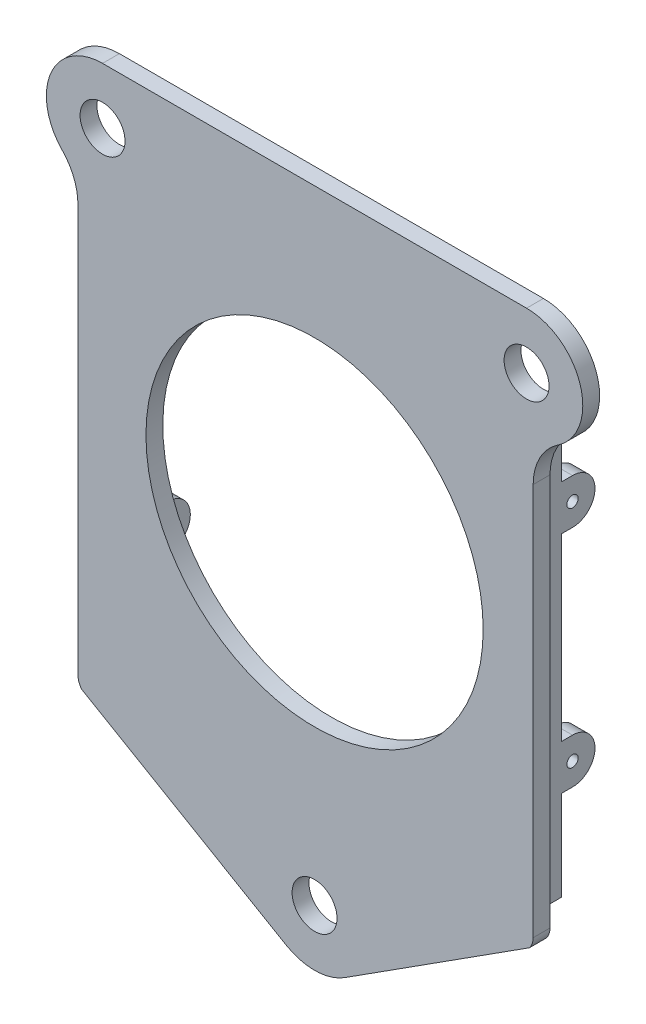
SolidWorks part; units mm, degrees
ref_plane "Front Plane" through (0, 0, 0) normal (0, 0, 1) x (1, 0, 0)
ref_plane "Top Plane" through (0, 0, 0) normal (0, 1, 0) x (1, 0, 0)
ref_plane "Right Plane" through (0, 0, 0) normal (1, 0, 0) x (0, 0, -1)
sketch "Sketch1" plane through (0, 0, 105.6016) normal (0, 0, 1) x (1, 0, 0)
  line L10 (93.8452, 26.6285) -> (97.7185, 26.6285)
  line L11 (98.3949, 28.5261) -> (98.3949, 105.9568)
  line L12 (95.3949, 108.9568) -> (20.3949, 108.9568)
  line L13 (17.3949, 105.9568) -> (17.3949, 28.5261)
  line L14 (18.0713, 26.6285) -> (21.9446, 26.6285)
  line L15 (21.9446, 26.6285) -> (20.8459, 27.9739)
  line L16 (20.3949, 29.239) -> (20.3949, 103.9568)
  line L17 (22.3949, 105.9568) -> (93.3949, 105.9568)
  line L18 (95.3949, 103.9568) -> (95.3949, 29.239)
  line L19 (94.944, 27.9739) -> (93.8452, 26.6285)
  line L20 (93.8452, 26.6285) -> (97.7185, 26.6285)
  line L21 (98.3949, 28.5261) -> (98.3949, 105.9568)
  line L22 (95.3949, 108.9568) -> (20.3949, 108.9568)
  line L23 (17.3949, 105.9568) -> (17.3949, 28.5261)
  line L24 (18.0713, 26.6285) -> (21.9446, 26.6285)
  line L25 (21.9446, 26.6285) -> (20.8459, 27.9739)
  line L26 (20.3949, 29.239) -> (20.3949, 103.9568)
  line L27 (22.3949, 105.9568) -> (93.3949, 105.9568)
  line L28 (95.3949, 103.9568) -> (95.3949, 29.239)
  line L29 (94.944, 27.9739) -> (93.8452, 26.6285)
  arc A8 (97.7185, 26.6285) -> (98.3949, 28.5261) centre (95.3949, 28.5261) ccw
  arc A9 (98.3949, 105.9568) -> (95.3949, 108.9568) centre (95.3949, 105.9568) ccw
  arc A10 (20.3949, 108.9568) -> (17.3949, 105.9568) centre (20.3949, 105.9568) ccw
  arc A11 (17.3949, 28.5261) -> (18.0713, 26.6285) centre (20.3949, 28.5261) ccw
  arc A12 (20.3949, 29.239) -> (20.8459, 27.9739) centre (22.3949, 29.239) ccw
  arc A13 (22.3949, 105.9568) -> (20.3949, 103.9568) centre (22.3949, 103.9568) ccw
  arc A14 (95.3949, 103.9568) -> (93.3949, 105.9568) centre (93.3949, 103.9568) ccw
  arc A15 (94.944, 27.9739) -> (95.3949, 29.239) centre (93.3949, 29.239) ccw
  arc A16 (97.7185, 26.6285) -> (98.3949, 28.5261) centre (95.3949, 28.5261) ccw
  arc A17 (98.3949, 105.9568) -> (95.3949, 108.9568) centre (95.3949, 105.9568) ccw
  arc A18 (20.3949, 108.9568) -> (17.3949, 105.9568) centre (20.3949, 105.9568) ccw
  arc A19 (17.3949, 28.5261) -> (18.0713, 26.6285) centre (20.3949, 28.5261) ccw
  arc A20 (20.3949, 29.239) -> (20.8459, 27.9739) centre (22.3949, 29.239) ccw
  arc A21 (22.3949, 105.9568) -> (20.3949, 103.9568) centre (22.3949, 103.9568) ccw
  arc A22 (95.3949, 103.9568) -> (93.3949, 105.9568) centre (93.3949, 103.9568) ccw
  arc A23 (94.944, 27.9739) -> (95.3949, 29.239) centre (93.3949, 29.239) ccw
  dimension "D1" = 0
extrude "Casing edge profile" add sketch "Sketch1" along normal blind 3
sketch "Sketch2" plane through (0, 0, 108.6016) normal (0, 0, 1) x (1, 0, 0)
  line L0 (97.2224, 124.9411) -> (21.7756, 124.9411)
  line L1 (97.7185, 26.6285) -> (64.8887, 5.6221)
  line L2 (18.0713, 26.6285) -> (54.4613, 5.4069)
  line L3 (98.3949, 28.5261) -> (98.3949, 105.9568) construction
  line L4 (98.3949, 28.5261) -> (98.3949, 98.3528)
  line L5 (17.3949, 105.9568) -> (17.3949, 28.5261) construction
  line L6 (17.3949, 105.9568) -> (17.3949, 28.5261)
  circle A0 centre (97.2224, 114.9411) radius 4 construction
  circle A1 centre (21.7756, 114.9411) radius 4 construction
  circle A2 centre (97.2224, 114.9411) radius 4
  circle A3 centre (21.7756, 114.9411) radius 4
  circle A4 centre (59.499, 14.0453) radius 4 construction
  circle A5 centre (59.499, 14.0453) radius 4
  arc A6 (54.4613, 5.4069) -> (64.8887, 5.6221) centre (59.499, 14.0453) ccw
  arc A7 (102.8087, 106.647) -> (97.2224, 124.9411) centre (97.2224, 114.9411) ccw
  arc A8 (21.7756, 124.9411) -> (17.3949, 105.9517) centre (21.7756, 114.9411) ccw
  circle A9 centre (59.499, 14.0453) radius 10 construction
  arc A10 (97.7185, 26.6285) -> (98.3949, 28.5261) centre (95.3949, 28.5261) ccw construction
  arc A11 (97.7185, 26.6285) -> (98.3949, 28.5261) centre (95.3949, 28.5261) ccw
  arc A12 (17.3949, 28.5261) -> (18.0713, 26.6285) centre (20.3949, 28.5261) ccw construction
  arc A13 (17.3949, 28.5261) -> (18.0713, 26.6285) centre (20.3949, 28.5261) ccw
  circle A14 centre (97.2224, 114.9411) radius 10 construction
  circle A15 centre (21.7756, 114.9411) radius 10 construction
  arc A16 (98.3949, 98.3528) -> (102.8087, 106.647) centre (108.3949, 98.3528) cw
  point P14 (429.1037, 262.7196)
  line M8 (94.944, 27.9739) -> (93.8452, 26.6285)
  line M9 (93.8452, 26.6285) -> (97.7185, 26.6285)
  arc M10 (97.7185, 26.6285) -> (98.3949, 28.5261) centre (95.3949, 28.5261) ccw
  line M11 (98.3949, 28.5261) -> (98.3949, 105.9568)
  arc M12 (98.3949, 105.9568) -> (95.3949, 108.9568) centre (95.3949, 105.9568) ccw
  line M13 (95.3949, 108.9568) -> (20.3949, 108.9568)
  arc M14 (20.3949, 108.9568) -> (17.3949, 105.9568) centre (20.3949, 105.9568) ccw
  line M15 (17.3949, 105.9568) -> (17.3949, 28.5261)
  arc M16 (17.3949, 28.5261) -> (18.0713, 26.6285) centre (20.3949, 28.5261) ccw
  line M17 (18.0713, 26.6285) -> (21.9446, 26.6285)
  line M18 (21.9446, 26.6285) -> (20.8459, 27.9739)
  arc M19 (20.8459, 27.9739) -> (20.3949, 29.239) centre (22.3949, 29.239) cw
  line M20 (20.3949, 29.239) -> (20.3949, 103.9568)
  arc M21 (20.3949, 103.9568) -> (22.3949, 105.9568) centre (22.3949, 103.9568) cw
  line M22 (22.3949, 105.9568) -> (93.3949, 105.9568)
  arc M23 (93.3949, 105.9568) -> (95.3949, 103.9568) centre (93.3949, 103.9568) cw
  line M24 (95.3949, 103.9568) -> (95.3949, 29.239)
  arc M25 (95.3949, 29.239) -> (94.944, 27.9739) centre (93.3949, 29.239) cw
  dimension "D2" = 10
  dimension "D1" = 6
extrude "Screwholes and other stuff" add sketch "Sketch2" against normal blind 3 contours A16 A7 L0 A8 A2 A3 M11 M15 M14 M13 M12 | L6 M25 M8 M9 M10 M11 M12 M13 M14 M15 M16 M17 M18 M19 M20 M21 M22 M23 M24 | L2 A6 L1 A5 M9 M8 M25 M24 M23 M22 M21 M20 M19 M18 M17
sketch "Sketch3" plane through (0, 0, 105.6016) normal (0, 0, -1) x (-1, 0, 0)
  line L0 (-20.3949, 103.9568) -> (-20.3949, 29.239) construction
  line L1 (-20.3949, 103.9568) -> (-20.3949, 29.239)
  line L2 (-93.3949, 105.9568) -> (-22.3949, 105.9568) construction
  line L3 (-93.3949, 105.9568) -> (-22.3949, 105.9568)
  line L4 (-95.3949, 29.239) -> (-95.3949, 103.9568) construction
  line L5 (-95.3949, 29.239) -> (-95.3949, 103.9568)
  line L6 (-23.3949, 102.9568) -> (-23.3949, 29.239)
  line L7 (-92.3949, 102.9568) -> (-23.3949, 102.9568)
  line L8 (-92.3949, 29.239) -> (-92.3949, 102.9568)
  line L9 (-95.3949, 29.239) -> (-92.3949, 29.239)
  line L10 (-23.3949, 29.239) -> (-20.3949, 29.239)
  arc A0 (-20.3949, 103.9568) -> (-22.3949, 105.9568) centre (-22.3949, 103.9568) ccw construction
  arc A1 (-20.3949, 103.9568) -> (-22.3949, 105.9568) centre (-22.3949, 103.9568) ccw
  arc A2 (-93.3949, 105.9568) -> (-95.3949, 103.9568) centre (-93.3949, 103.9568) ccw construction
  arc A3 (-93.3949, 105.9568) -> (-95.3949, 103.9568) centre (-93.3949, 103.9568) ccw
  arc A4 (-23.3949, 102.9568) -> (-23.3949, 102.9568) centre (-23.3949, 102.9568) ccw
  arc A5 (-92.3949, 102.9568) -> (-92.3949, 102.9568) centre (-92.3949, 102.9568) ccw
  dimension "D1" = 3
extrude "Casing lip" add sketch "Sketch3" along normal blind 5
fillet "Casing lip fillet 2mm" radius 2 5 edges at (23.3949, 66.0979, 105.6016) (23.3949, 102.9568, 103.1016) (57.8949, 102.9568, 105.6016) (92.3949, 66.0979, 105.6016) (92.3949, 102.9568, 103.1016)
fillet "Fillet I missed in screwhole et al. sketch" radius 10 1 edges at (17.3949, 105.9517, 107.1016)
sketch "Sketch4" plane through (95.3949, 0, 0) normal (1, 0, 0) x (0, 0, -1)
  line L0 (-105.6016, 28.5261) -> (-105.6016, 98.3528) construction
  line L1 (-100.6016, 29.239) -> (-105.6016, 29.239) construction
  line L2 (-100.6016, 103.9568) -> (-100.6016, 29.239) construction
  line L3 (-100.6016, 93.239) -> (-100.6016, 85.239)
  line L4 (-98.6016, 93.239) -> (-100.6016, 93.239)
  line L5 (-98.6016, 85.239) -> (-100.6016, 85.239)
  line L6 (-98.6016, 45.239) -> (-100.6016, 45.239)
  line L7 (-100.6016, 45.239) -> (-100.6016, 53.239)
  line L8 (-100.6016, 53.239) -> (-98.6016, 53.239)
  line L9 (-100.6016, 53.239) -> (-100.6016, 45.239)
  circle A0 centre (-98.6016, 49.239) radius 1
  circle A1 centre (-98.6016, 89.239) radius 1
  arc A3 (-98.6016, 45.239) -> (-98.6016, 53.239) centre (-98.6016, 49.239) ccw
  circle A4 centre (-98.6016, 49.239) radius 4 construction
  arc A5 (-98.6016, 85.239) -> (-98.6016, 93.239) centre (-98.6016, 89.239) ccw
  point P8 (-100.6016, 53.239)
  line M7 (-100.6016, 29.239) -> (-100.6016, 103.9568)
  dimension "D1" = 2
  dimension "D6" = 3
  dimension "D2" = 7
  dimension "D3" = 20
  dimension "D4" = 40
  dimension "D5" = 3
extrude "Side screwholes 1" add sketch "Sketch4" against normal up to surface (3 mm away) contours L5 A5 L4 A1 M7 | L6 A3 L8 A0 M7 up to face at (92.3949, 65.0979, 102.1016)
sketch "Sketch6" plane through (20.3949, 0, 0) normal (-1, 0, 0) x (0, 0, 1)
  line L22 (100.6016, 29.239) -> (103.6016, 29.239)
  line L23 (103.6016, 29.239) -> (103.6016, 100.9568)
  line L24 (103.6016, 100.9568) -> (100.6016, 100.9568)
  line L25 (100.6016, 100.9568) -> (100.6016, 93.239)
  line L26 (100.6016, 93.239) -> (98.6016, 93.239)
  line L27 (98.6016, 85.239) -> (100.6016, 85.239)
  line L28 (100.6016, 85.239) -> (100.6016, 53.239)
  line L29 (100.6016, 53.239) -> (98.6016, 53.239)
  line L30 (98.6016, 45.239) -> (100.6016, 45.239)
  line L31 (100.6016, 45.239) -> (100.6016, 29.239)
  line L32 (100.6016, 29.239) -> (103.6016, 29.239)
  line L33 (103.6016, 29.239) -> (103.6016, 100.9568)
  line L34 (103.6016, 100.9568) -> (100.6016, 100.9568)
  line L35 (100.6016, 100.9568) -> (100.6016, 93.239)
  line L36 (100.6016, 93.239) -> (98.6016, 93.239)
  line L37 (98.6016, 85.239) -> (100.6016, 85.239)
  line L38 (100.6016, 85.239) -> (100.6016, 53.239)
  line L39 (100.6016, 53.239) -> (98.6016, 53.239)
  line L40 (98.6016, 45.239) -> (100.6016, 45.239)
  line L41 (100.6016, 45.239) -> (100.6016, 29.239)
  circle A1 centre (98.6016, 49.239) radius 1 construction
  circle A3 centre (98.6016, 89.239) radius 1 construction
  arc A8 (98.6016, 93.239) -> (98.6016, 85.239) centre (98.6016, 89.239) ccw
  arc A9 (98.6016, 53.239) -> (98.6016, 45.239) centre (98.6016, 49.239) ccw
  arc A10 (98.6016, 93.239) -> (98.6016, 85.239) centre (98.6016, 89.239) ccw
  arc A11 (98.6016, 53.239) -> (98.6016, 45.239) centre (98.6016, 49.239) ccw
  circle A12 centre (98.6016, 49.239) radius 1
  circle A13 centre (98.6016, 89.239) radius 1
  dimension "D1" = 0
extrude "Side screwholes 2" add sketch "Sketch6" against normal up to surface (3 mm away)
sketch "Sketch7" plane through (0, 105.9568, 0) normal (0, 1, 0) x (1, 0, 0)
  line L0 (22.3949, -100.6016) -> (93.3949, -100.6016) construction
  line L1 (39.3949, -100.6016) -> (47.3949, -100.6016)
  line L3 (92.3949, -94.6016) -> (92.3949, -98.6016) construction
  line L4 (39.3949, -98.6016) -> (39.3949, -100.6016)
  line L5 (47.3949, -98.6016) -> (47.3949, -100.6016)
  line L6 (68.3949, -98.6016) -> (68.3949, -100.6016)
  line L7 (76.3949, -98.6016) -> (76.3949, -100.6016)
  line L8 (68.3949, -100.6016) -> (76.3949, -100.6016)
  line L9 (23.3949, -98.6016) -> (23.3949, -94.6016) construction
  circle A0 centre (43.3949, -98.6016) radius 1
  circle A1 centre (72.3949, -98.6016) radius 1
  arc A2 (47.3949, -98.6016) -> (39.3949, -98.6016) centre (43.3949, -98.6016) ccw
  arc A3 (76.3949, -98.6016) -> (68.3949, -98.6016) centre (72.3949, -98.6016) ccw
  circle A4 centre (43.3949, -98.6016) radius 4 construction
  circle A5 centre (72.3949, -98.6016) radius 4 construction
  dimension "D2" = 2
  dimension "D1" = 2
  dimension "D3" = 20
  dimension "D4" = 2
  dimension "D5" = 20
  dimension "D6" = 3
extrude "Top screwholes" add sketch "Sketch7" against normal up to surface (3 mm away) up to face at (57.8949, 102.9568, 102.1016)
sketch "Sketch9" plane through (0, 0, 108.6016) normal (0, 0, 1) x (1, 0, 0)
  circle A0 centre (59.499, 71.5453) radius 30
  dimension "D1" = 60
extrude "Camera hole" cut sketch "Sketch9" against normal through all both and the other way through all
